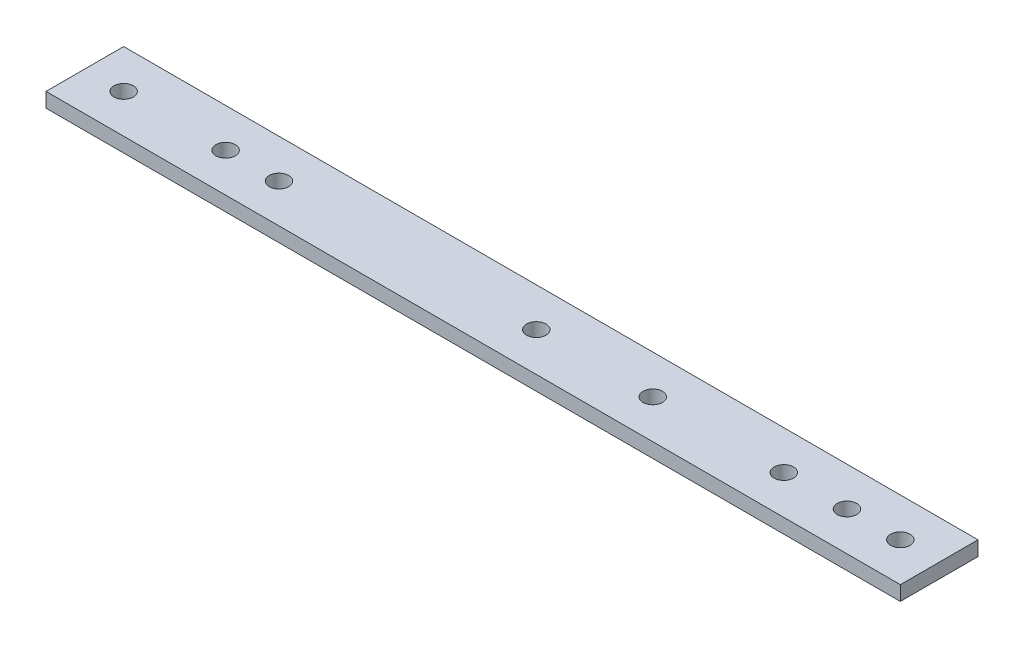
SolidWorks part; units mm, degrees
material "6061-T6 (SS)"
ref_plane "Front Plane" through (0, 0, 0) normal (0, 0, 1) x (1, 0, 0)
ref_plane "Top Plane" through (0, 0, 0) normal (0, 1, 0) x (1, 0, 0)
ref_plane "Right Plane" through (0, 0, 0) normal (1, 0, 0) x (0, 0, -1)
sketch "Sketch1" plane through (0, 0, 0) normal (0, 1, 0) x (1, 0, 0)
  line L1 (139.7, -12.7) -> (-139.7, -12.7)
  line L2 (139.7, -12.7) -> (139.7, 12.7)
  line L3 (139.7, 12.7) -> (-139.7, 12.7)
  line L4 (-139.7, -12.7) -> (-139.7, 12.7)
  line L5 (139.7, -12.7) -> (-139.7, 12.7) construction
  line L6 (139.7, 12.7) -> (-139.7, -12.7) construction
  point P0 (0, 0)
  dimension "D1" = 279.4
  dimension "D2" = 25.4
extrude "Boss-Extrude1" add sketch "Sketch1" along normal blind 4.7625
sketch "Sketch8" plane through (0, 4.7625, 0) normal (0, 1, 0) x (1, 0, 0)
  line L0 (139.7, -12.7) -> (139.7, 12.7) construction
  line L1 (-139.7, 12.7) -> (-139.7, -12.7) construction
  line L2 (-139.7, 0) -> (139.7, 0) construction
  line L3 (-139.7, -12.7) -> (139.7, -12.7) construction
  circle A0 centre (127, 0) radius 3.175
  circle A1 centre (109.5375, 0) radius 3.175
  circle A2 centre (88.9, 0) radius 3.175
  circle A3 centre (46.0375, 0) radius 3.175
  circle A4 centre (7.9375, 0) radius 3.175
  circle A5 centre (-76.2, 0) radius 3.175
  circle A6 centre (-127, 0) radius 3.175
  circle A7 centre (-93.6625, 0) radius 3.175
  dimension "D1" = 6.35
  dimension "D2" = 6.35
  dimension "D3" = 6.35
  dimension "D4" = 6.35
  dimension "D5" = 6.35
  dimension "D6" = 6.35
  dimension "D7" = 6.35
  dimension "D8" = 6.35
  dimension "D9" = 12.7
  dimension "D10" = 30.1625
  dimension "D11" = 50.8
  dimension "D12" = 93.6625
  dimension "D13" = 131.7625
  dimension "D14" = 215.9
  dimension "D15" = 233.3625
  dimension "D16" = 266.7
  dimension "D17" = 12.7
extrude "Cut-Extrude6" cut sketch "Sketch8" against normal up to surface (4.7625 mm away) up to face at (0, 0, 0)
